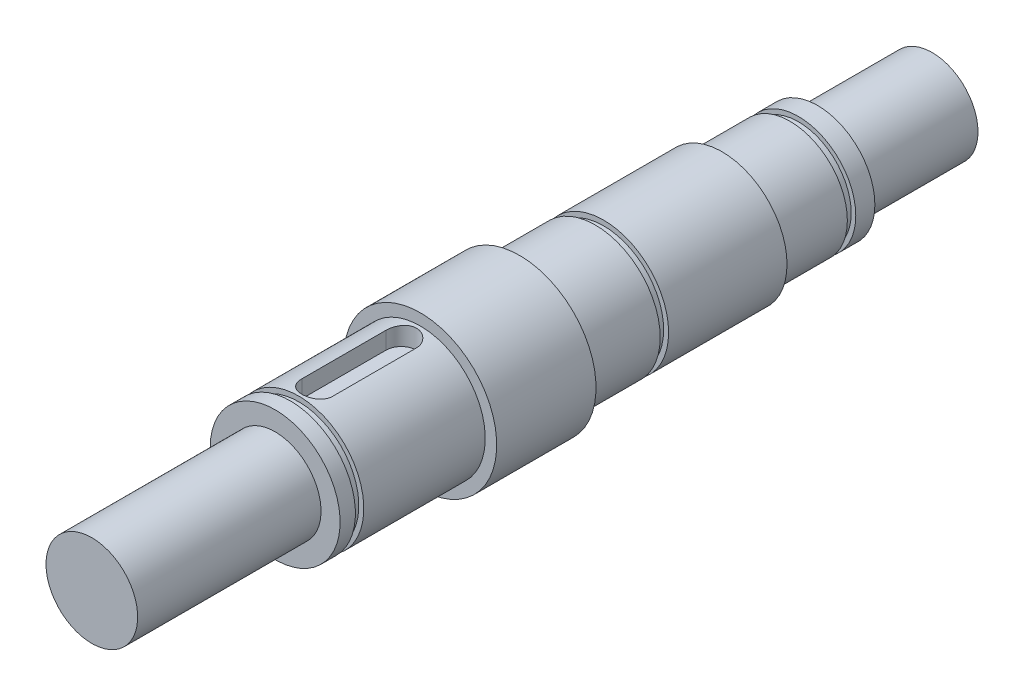
SolidWorks part; units mm, degrees
material "Plain Carbon Steel"
ref_plane "Front Plane" through (0, 0, 0) normal (0, 0, 1) x (1, 0, 0)
ref_plane "Top Plane" through (0, 0, 0) normal (0, 1, 0) x (1, 0, 0)
ref_plane "Right Plane" through (0, 0, 0) normal (1, 0, 0) x (0, 0, -1)
sketch "Sketch1" plane through (0, 0, 0) normal (0, 0, 1) x (1, 0, 0)
  circle A0 centre (0, 0) radius 10
  dimension "D1" = 20
extrude "Boss-Extrude1" add sketch "Sketch1" along normal mid plane 122
sketch "Sketch3" plane through (0, 0, 0) normal (1, 0, 0) x (0, 0, -1)
  line L0 (0, 0) -> (68.127, 0) construction
  line L1 (-5, 10) -> (-5, 8.5)
  line L2 (61, 10) -> (-61, 10) construction
  line L3 (-5, 8.5) -> (61, 8.5)
  line L4 (61, -10) -> (61, 10) construction
  line L5 (61, 8.5) -> (61, 10)
  line L6 (61, 10) -> (-5, 10)
  dimension "D1" = 5
  dimension "D2" = 8.5
revolve "Cut-Revolve1" cut sketch "Sketch3" angle 360 about L0
sketch "Sketch4" plane through (0, 0, 0) normal (1, 0, 0) x (0, 0, -1)
  line L0 (0, 0) -> (-82.0475, 0) construction
  line L1 (-18, 10) -> (-18, 8.5)
  line L2 (-5, 10) -> (-61, 10) construction
  line L3 (-18, 8.5) -> (-61, 8.5)
  line L4 (-61, 10) -> (-61, -10) construction
  line L5 (-61, 8.5) -> (-61, 10)
  line L6 (-61, 10) -> (-18, 10)
  line L7 (-5, -10) -> (-5, 10) construction
  dimension "D1" = 8.5
  dimension "D2" = 13
revolve "Cut-Revolve2" cut sketch "Sketch4" angle 360 about L0
sketch "Sketch5" plane through (0, 0, 0) normal (1, 0, 0) x (0, 0, -1)
  line L0 (0, 0) -> (-76.3333, 0) construction
  line L1 (-37, 8.5) -> (-37, 6)
  line L2 (-18, 8.5) -> (-61, 8.5) construction
  line L3 (-37, 6) -> (-61, 6)
  line L4 (-61, 8.5) -> (-61, -8.5) construction
  line L5 (-61, 6) -> (-61, 8.5)
  line L6 (-61, 8.5) -> (-37, 8.5)
  line L7 (-18, 10) -> (-18, -10) construction
  dimension "D1" = 19
  dimension "D2" = 6
revolve "Cut-Revolve3" cut sketch "Sketch5" angle 360 about L0
sketch "Sketch6" plane through (0, 0, 0) normal (1, 0, 0) x (0, 0, -1)
  line L0 (0, 0) -> (67.4924, 0) construction
  line L1 (21.5, 8.5) -> (21.5, 7.5)
  line L2 (61, 8.5) -> (-5, 8.5) construction
  line L3 (21.5, 7.5) -> (61, 7.5)
  line L4 (61, -8.5) -> (61, 8.5) construction
  line L5 (61, 7.5) -> (61, 8.5)
  line L6 (61, 8.5) -> (21.5, 8.5)
  line L7 (-5, -8.5) -> (-5, 8.5) construction
  dimension "D1" = 7.5
  dimension "D2" = 26.5
revolve "Cut-Revolve4" cut sketch "Sketch6" angle 360 about L0
sketch "Sketch7" plane through (0, 0, 0) normal (1, 0, 0) x (0, 0, -1)
  line L0 (0, 0) -> (68.3549, 0) construction
  line L1 (34, 7.5) -> (34, 6)
  line L2 (61, 7.5) -> (21.5, 7.5) construction
  line L3 (34, 6) -> (61, 6)
  line L4 (61, -7.5) -> (61, 7.5) construction
  line L5 (61, 6) -> (61, 7.5)
  line L6 (61, 7.5) -> (34, 7.5)
  line L7 (21.5, -8.5) -> (21.5, 8.5) construction
  dimension "D1" = 6
  dimension "D2" = 12.5
revolve "Cut-Revolve5" cut sketch "Sketch7" angle 360 about L0
sketch "Sketch8" plane through (0, 0, 0) normal (1, 0, 0) x (0, 0, -1)
  line L0 (0, 0) -> (72.0206, 0) construction
  line L1 (30.4, 7.5) -> (30.4, 6.9)
  line L2 (34, 7.5) -> (21.5, 7.5) construction
  line L3 (30.4, 6.9) -> (31.5, 6.9)
  line L4 (31.5, 6.9) -> (31.5, 7.5)
  line L5 (31.5, 7.5) -> (30.4, 7.5)
  line L6 (21.5, -8.5) -> (21.5, 8.5) construction
  dimension "D1" = 10
  dimension "D2" = 1.1
  dimension "D3" = 6.9
revolve "Cut-Revolve6" cut sketch "Sketch8" angle 360 about L0
sketch "Sketch9" plane through (0, 0, 0) normal (1, 0, 0) x (0, 0, -1)
  line L0 (0, 0) -> (88.0894, 0) construction
  line L1 (4.9, 8.5) -> (4.9, 7.85)
  line L2 (21.5, 8.5) -> (-5, 8.5) construction
  line L3 (4.9, 7.85) -> (6, 7.85)
  line L4 (6, 7.85) -> (6, 8.5)
  line L5 (6, 8.5) -> (4.9, 8.5)
  line L6 (-5, -10) -> (-5, 10) construction
  dimension "D1" = 11
  dimension "D2" = 1.1
  dimension "D3" = 7.85
revolve "Cut-Revolve7" cut sketch "Sketch9" angle 360 about L0
sketch "Sketch10" plane through (0, 0, 0) normal (1, 0, 0) x (0, 0, -1)
  line L0 (0, 0) -> (-65.6962, 0) construction
  line L1 (-35, 8.5) -> (-35, 7.85)
  line L2 (-18, 8.5) -> (-37, 8.5) construction
  line L3 (-35, 7.85) -> (-33.9, 7.85)
  line L4 (-33.9, 7.85) -> (-33.9, 8.5)
  line L5 (-33.9, 8.5) -> (-35, 8.5)
  line L6 (-37, 8.5) -> (-37, -8.5) construction
  dimension "D1" = 2
  dimension "D2" = 1.1
  dimension "D3" = 7.85
revolve "Cut-Revolve8" cut sketch "Sketch10" angle 360 about L0
sketch "Sketch11" plane through (0, 0, 0) normal (1, 0, 0) x (0, 0, -1)
  line L0 (34, -6) -> (61, -6) construction
  line L1 (61, 6) -> (49, 6)
  line L2 (61, 6) -> (61, -6)
  line L3 (61, -6) -> (49, -6)
  line L4 (49, 6) -> (49, -6)
  dimension "D1" = 12
extrude "Cut-Extrude1" cut sketch "Sketch11" against normal through all both and the other way through all
ref_plane "Plane1" through (0, 8.5, 0) normal (0, 1, 0) x (1, 0, 0)
sketch "Sketch12" plane through (0, 8.5, 0) normal (0, 1, 0) x (1, 0, 0)
  line L0 (0, 0) -> (0, -71.2472) construction
  line L1 (0, -26) -> (15.1697, -26) construction
  line L2 (2, -31.5) -> (2, -20.5)
  line L3 (-2, -31.5) -> (-2, -20.5)
  line L4 (-10, -18) -> (10, -18) construction
  arc A0 (2, -20.5) -> (-2, -20.5) centre (0, -20.5) ccw
  arc A1 (2, -31.5) -> (-2, -31.5) centre (0, -31.5) cw
  point P10 (2, -26)
  dimension "D1" = 4
  dimension "D2" = 11
  dimension "D3" = 8
extrude "Cut-Extrude2" cut sketch "Sketch12" against normal blind 2.5
